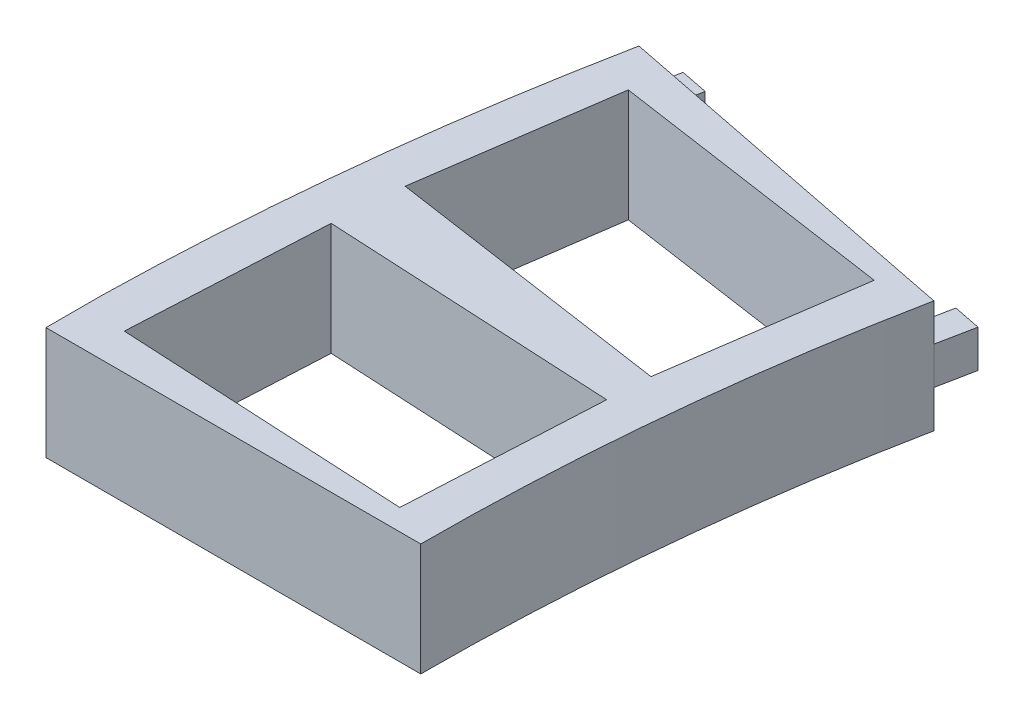
SolidWorks part; units mm, degrees
ref_plane "Front Plane" through (0, 0, 0) normal (0, 0, 1) x (1, 0, 0)
ref_plane "Top Plane" through (0, 0, 0) normal (0, 1, 0) x (1, 0, 0)
ref_plane "Right Plane" through (0, 0, 0) normal (1, 0, 0) x (0, 0, -1)
sketch "Sketch1" plane through (0, 0, 0) normal (0, 1, 0) x (1, 0, 0)
  line L0 (0, -1585.8629) -> (0, 77707.2829) construction
  line L1 (-1585.8629, 0) -> (77707.2829, 0) construction
  line L3 (-289.5179, 57.5887) -> (-250.2864, 49.7851)
  line L38 (-250.2864, 49.7851) -> (0, 0) construction
  line L58 (-295.1278, 6.0543) -> (-295.1278, 0)
  line L64 (-295.1278, 0) -> (-255.1898, 0)
  line L97 (-255.3649, 48.5012) -> (-258.3626, 27.7162)
  line L98 (-258.3626, 27.7162) -> (-289.0385, 32.1867)
  line L99 (-289.0385, 32.1867) -> (-286.0409, 52.9716)
  line L100 (-286.0409, 52.9716) -> (-255.3649, 48.5012)
  line L101 (-258.5962, 23.2223) -> (-259.6749, 2.25)
  line L102 (-259.6749, 2.25) -> (-290.6335, 3.85)
  line L103 (-290.6335, 3.85) -> (-289.5549, 24.8223)
  line L104 (-289.5549, 24.8223) -> (-258.5962, 23.2223)
  arc A1 (-295.1278, 6.0543) -> (-289.5179, 57.5887) centre (0, 0) cw
  arc A3 (-250.2864, 49.7851) -> (-255.1898, 0) centre (0, 0) ccw
  point P15 (-258.5962, 23.2223)
  point P34 (-258.3626, 27.7162)
  point P35 (-258.5962, 23.2223)
  point P36 (-258.3626, 27.7162)
  dimension "D1" = 11.25
  dimension "D2" = 2.25
  dimension "D14" = 4.5
  dimension "D3" = 2.25
  dimension "D6" = 31
  dimension "D7" = 31
  dimension "D8" = 31
  dimension "D9" = 31
  dimension "D4" = 21
  dimension "D5" = 21
  dimension "D10" = 31
  dimension "D12" = 21
  dimension "D13" = 21
  dimension "D11" = 31
extrude "Boss-Extrude1" add sketch "Sketch1" along normal blind 12
ref_plane "Plane1" through (-255.1898, 0, 0) normal (1, 0, 0) x (0, 0, -1)
ref_plane "Plane3" through (-255.1898, 0, 0) normal (1, 0, 0) x (0, 0, -1)
ref_plane "Plane4" through (-275.1898, 0, 0) normal (1, 0, 0) x (0, 0, -1)
ref_plane "Plane6" through (-250.2864, 0, -49.7851) normal (0.9808, 0, 0.1951) x (0.1951, 0, -0.9808)
sketch "Sketch4" plane through (-250.2864, 0, -49.7851) normal (0.9808, 0, 0.1951) x (0.1951, 0, -0.9808)
  line L0 (-0.6997, 12) -> (0, 12)
  line L1 (0, 12) -> (-49.7851, 12) construction
  line L2 (0, 12) -> (0, 8)
  line L3 (0, 12) -> (0, 0) construction
  line L4 (0, 8) -> (4, 8)
  line L5 (4, 8) -> (4, 4)
  line L6 (4, 4) -> (0, 4)
  line L7 (0, 4) -> (0, 0)
  line L8 (0, 0) -> (-0.6997, 0)
  line L9 (-49.7851, 0) -> (0, 0) construction
  line L10 (-0.6997, 0) -> (-0.6997, 12)
  dimension "D1" = 4
  dimension "D2" = 4
  dimension "D3" = 4
extrude "Boss-Extrude2" add sketch "Sketch4" against normal blind 3
ref_plane "Plane7" through (-269.9021, 0, -53.6869) normal (0.9808, 0, 0.1951) x (0.1951, 0, -0.9808)
mirror "Mirror3" about plane through (-269.9021, 0, -53.6869) normal (0.9808, 0, 0.1951) of "Boss-Extrude2"
sketch "Sketch5" plane through (0, 0, 0) normal (0, 0, 1) x (1, 0, 0)
  line L0 (-255.1898, 8) -> (-259.1898, 8)
  line L1 (-255.1898, 12) -> (-255.1898, 0) construction
  line L2 (-259.1898, 8) -> (-259.1898, 4)
  line L3 (-259.1898, 4) -> (-255.1898, 4)
  line L4 (-255.1898, 4) -> (-255.1898, 8)
  dimension "D1" = 4
  dimension "D2" = 4
  dimension "D3" = 4
